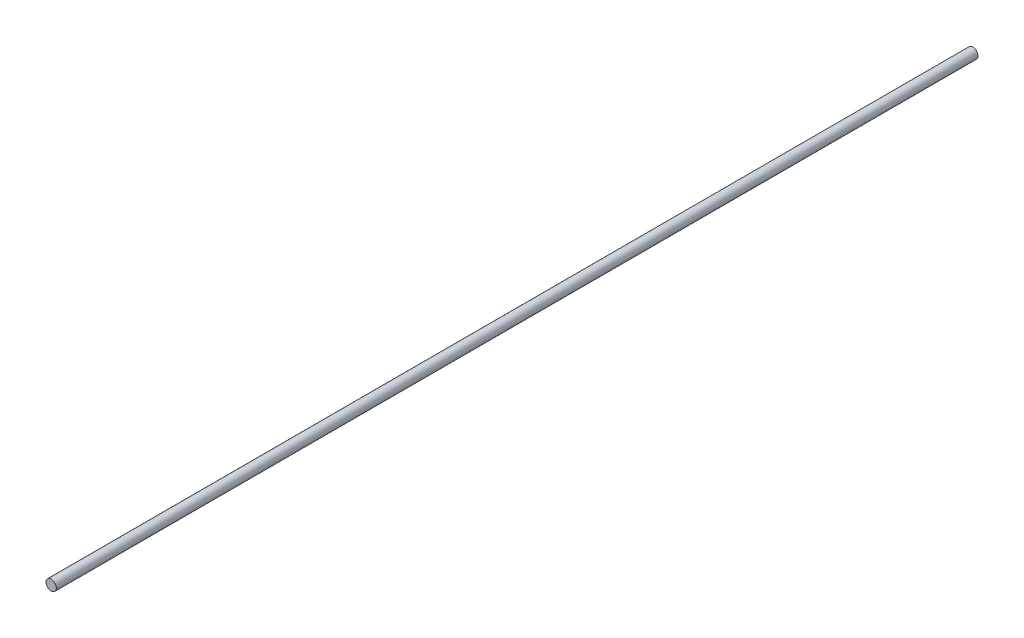
SolidWorks part; units mm, degrees
ref_plane "Plano frontal" through (0, 0, 0) normal (0, 0, 1) x (1, 0, 0)
ref_plane "Plano superior" through (0, 0, 0) normal (0, 1, 0) x (1, 0, 0)
ref_plane "Plano direito" through (0, 0, 0) normal (1, 0, 0) x (0, 0, -1)
sketch "Esboço1" plane through (0, 0, 0) normal (0, 0, 1) x (1, 0, 0)
  circle A0 centre (0, 0) radius 3.815
  dimension "D1" = 7.63
extrude "Ressalto-extrusão1" add sketch "Esboço1" along normal blind 681
